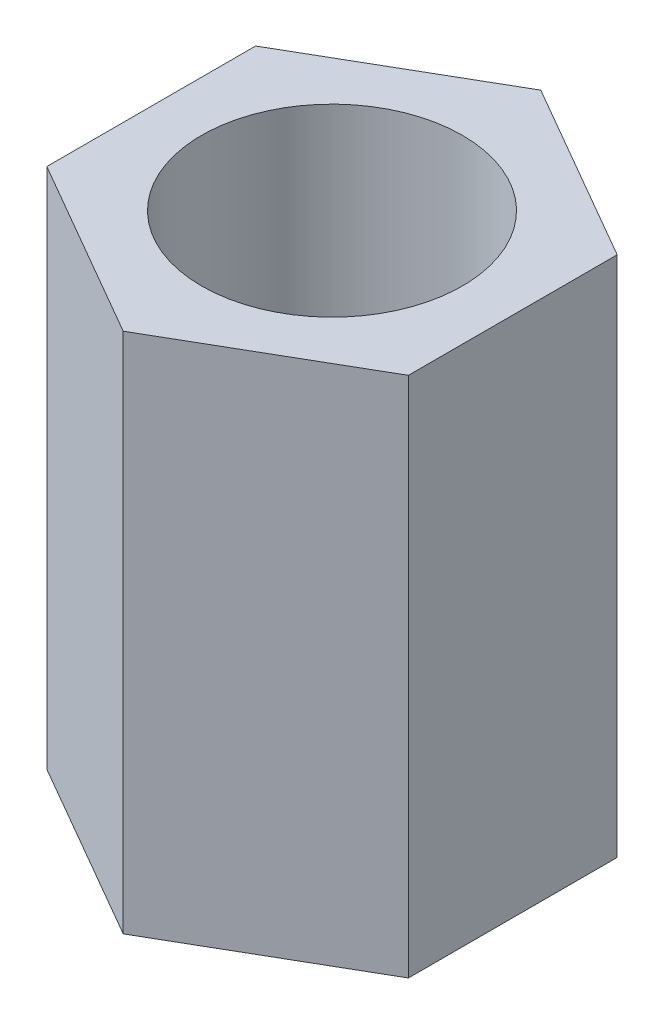
SolidWorks part; units mm, degrees
material "黄铜"
ref_plane "前视基准面" through (0, 0, 0) normal (0, 0, 1) x (1, 0, 0)
ref_plane "上视基准面" through (0, 0, 0) normal (0, 1, 0) x (1, 0, 0)
ref_plane "右视基准面" through (0, 0, 0) normal (1, 0, 0) x (0, 0, -1)
other "Configuration Table"
sketch "草图1" plane through (0, 0, 0) normal (0, 1, 0) x (1, 0, 0)
  line L1 (0, 2) -> (-1.7321, 1)
  line L2 (-1.7321, 1) -> (-1.7321, -1)
  line L3 (-1.7321, -1) -> (0, -2)
  line L4 (0, -2) -> (1.7321, -1)
  line L5 (1.7321, -1) -> (1.7321, 1)
  line L6 (1.7321, 1) -> (0, 2)
  circle A0 centre (0, 0) radius 1.25
  circle A1 centre (0, 0) radius 1.7321 construction
  dimension "D1" = 2.5
  dimension "D2" = 4
extrude "凸台-拉伸1" add sketch "草图1" along normal blind 5
